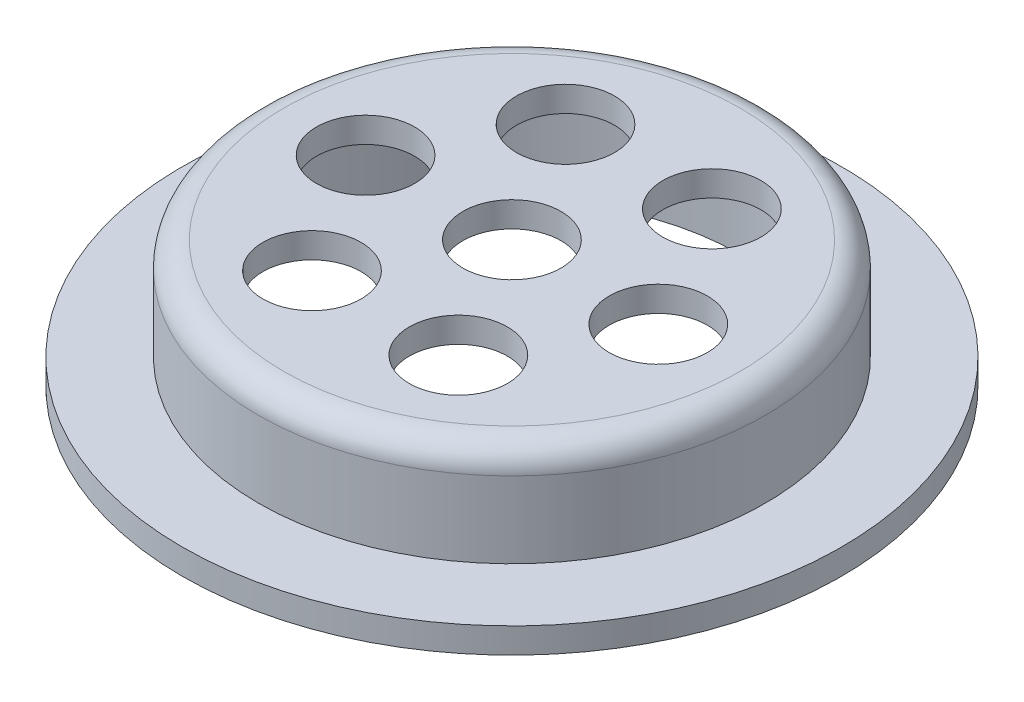
SolidWorks part; units mm, degrees
ref_plane "Front" through (0, 0, 0) normal (0, 0, 1) x (1, 0, 0)
ref_plane "Top" through (0, 0, 0) normal (0, 1, 0) x (1, 0, 0)
ref_plane "Right" through (0, 0, 0) normal (1, 0, 0) x (0, 0, -1)
sketch "草图1" plane through (0, 0, 0) normal (0, 0, 1) x (1, 0, 0)
  line L0 (0, 2.3622) -> (0, -3.0051) construction
  line L1 (0, 0.8) -> (1, 0.8)
  line L2 (1, 0.8) -> (1, 0.4)
  line L3 (1, 0.4) -> (1.3, 0.4)
  line L4 (1.3, 0.4) -> (1.3, 0.3)
  line L5 (1.3, 0.3) -> (0.9, 0.3)
  line L6 (0, 0.7) -> (0.9, 0.7)
  line L7 (0.9, 0.7) -> (0.9, 0.3)
  line L8 (0, 0.7) -> (0, 0.8)
  dimension "D1" = 1
  dimension "D2" = 0.3
  dimension "D3" = 0.5
  dimension "D4" = 0.1
  dimension "D5" = 0.1
  dimension "D6" = 0.1
revolve "旋转1" add sketch "草图1" angle 360 about L0
fillet "圆角3" radius 0.1 1 edges at (0, 0.8, 1)
sketch "草图2" plane through (0, 0.8, 0) normal (0, 1, 0) x (1, 0, 0)
  line L1 (-0.2887, 0.5) -> (-0.5774, 0) construction
  line L2 (-0.5774, 0) -> (-0.2887, -0.5) construction
  line L3 (-0.2887, -0.5) -> (0.2887, -0.5) construction
  line L4 (0.2887, -0.5) -> (0.5774, 0) construction
  line L5 (0.5774, 0) -> (0.2887, 0.5) construction
  line L6 (0.2887, 0.5) -> (-0.2887, 0.5) construction
  circle A0 centre (0, 0) radius 0.5 construction
  circle A1 centre (0, 0) radius 0.1936
  circle A2 centre (-0.2887, 0.5) radius 0.1936
  circle A3 centre (0.2887, 0.5) radius 0.1936
  circle A4 centre (0.5774, 0) radius 0.1936
  circle A5 centre (0.2887, -0.5) radius 0.1936
  circle A6 centre (-0.2887, -0.5) radius 0.1936
  circle A7 centre (-0.5774, 0) radius 0.1936
  point P13 (-0.2452, 0.45)
  point P24 (0, 0)
  dimension "D1" = 6
  dimension "D2" = 0.5
extrude "切除-拉伸1" cut sketch "草图2" against normal through all
